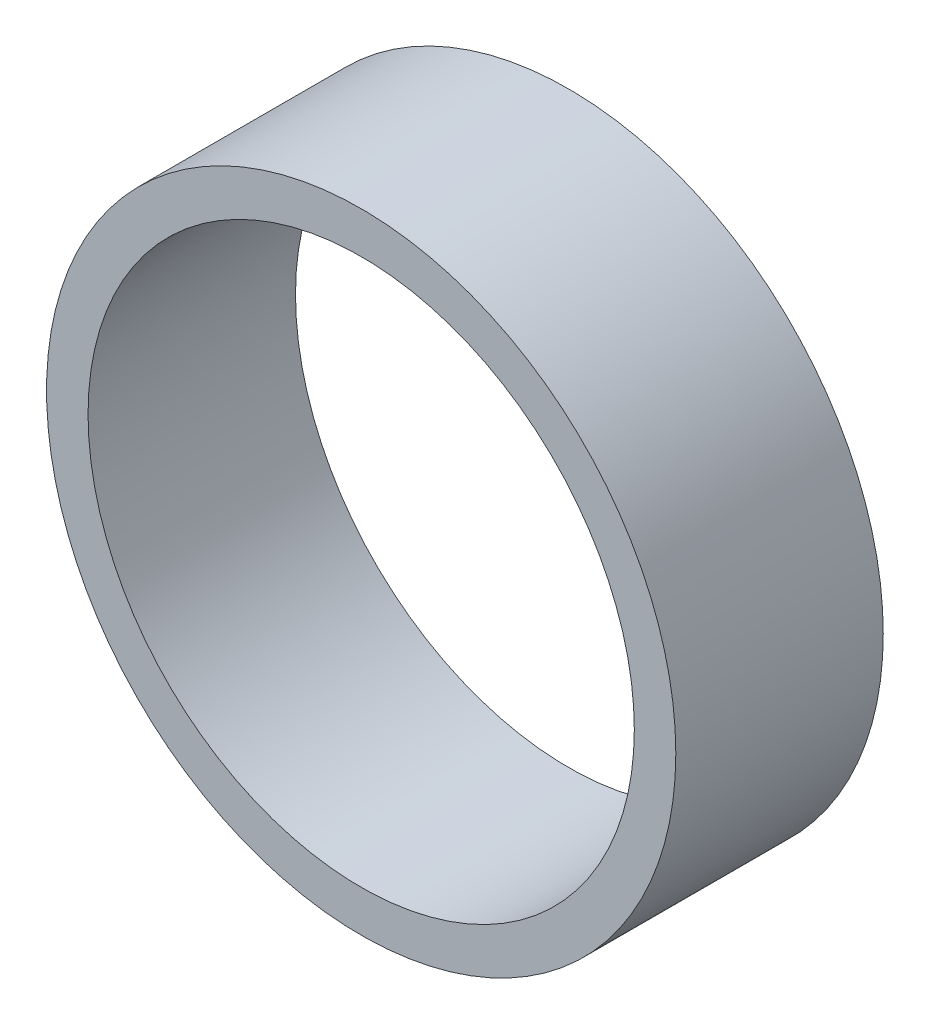
SolidWorks part; units mm, degrees
ref_plane "Front Plane" through (0, 0, 0) normal (0, 0, 1) x (1, 0, 0)
ref_plane "Top Plane" through (0, 0, 0) normal (0, 1, 0) x (1, 0, 0)
ref_plane "Right Plane" through (0, 0, 0) normal (1, 0, 0) x (0, 0, -1)
sketch "Sketch1" plane through (0, 0, 0) normal (0, 0, 1) x (1, 0, 0)
  circle A0 centre (0, 0) radius 22.75
  dimension "D1" = 45.5
extrude "Boss-Extrude1" add sketch "Sketch1" along normal blind 15
sketch "Sketch2" plane through (0, 0, 15) normal (0, 0, 1) x (1, 0, 0)
  circle A0 centre (0, 0) radius 19.75
  circle A1 centre (0, 0) radius 22.75 construction
  dimension "D1" = 3
extrude "Cut-Extrude1" cut sketch "Sketch2" against normal through all
